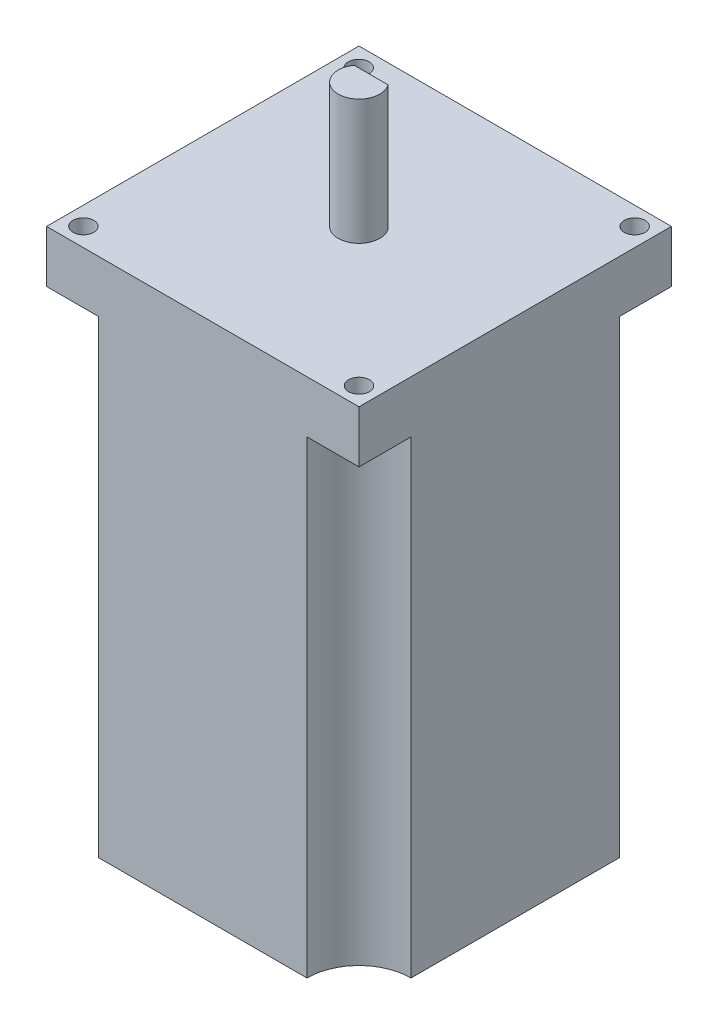
SolidWorks part; units mm, degrees
ref_plane "Front Plane" through (0, 0, 0) normal (0, 0, 1) x (1, 0, 0)
ref_plane "Top Plane" through (0, 0, 0) normal (0, 1, 0) x (1, 0, 0)
ref_plane "Right Plane" through (0, 0, 0) normal (1, 0, 0) x (0, 0, -1)
sketch "Sketch1" plane through (0, 0, 0) normal (0, 1, 0) x (1, 0, 0)
  line L1 (-20, 30) -> (20, 30)
  line L2 (-30, 20) -> (-30, -20)
  line L3 (-20, -30) -> (20, -30)
  line L4 (30, 20) -> (30, -20)
  line L5 (-30, 30) -> (30, -30) construction
  line L6 (-30, -30) -> (30, 30) construction
  arc A0 (-30, 20) -> (-20, 30) centre (-30, 30) ccw
  arc A1 (20, -30) -> (30, -20) centre (30, -30) cw
  arc A2 (20, 30) -> (30, 20) centre (30, 30) ccw
  arc A3 (-30, -20) -> (-20, -30) centre (-30, -30) cw
  point P0 (0, 0)
  dimension "D1" = 20
  dimension "D2" = 20
extrude "Boss-Extrude3" add sketch "Sketch1" along normal blind 90
sketch "Sketch3" plane through (0, 90, 0) normal (0, 1, 0) x (1, 0, 0)
  line L1 (-30, 30) -> (30, 30)
  line L2 (-30, 30) -> (-30, -30)
  line L3 (-30, -30) -> (30, -30)
  line L4 (30, 30) -> (30, -30)
  line L5 (-30, 30) -> (30, -30) construction
  line L6 (-30, -30) -> (30, 30) construction
  point P0 (0, 0)
extrude "Boss-Extrude4" add sketch "Sketch3" along normal blind 10
sketch "Sketch4" plane through (0, 100, 0) normal (0, 1, 0) x (1, 0, 0)
  line L0 (-3.25, 2.3318) -> (3.25, 2.3318)
  arc A0 (-3.25, 2.3318) -> (3.25, 2.3318) centre (0, 0) ccw
  dimension "D1" = 8
extrude "Boss-Extrude5" add sketch "Sketch4" along normal blind 24
sketch "Sketch6" plane through (0, 90, 0) normal (0, -1, 0) x (1, 0, 0)
  line L0 (-30, -30) -> (-22.9835, -22.8748) construction
  line L1 (-29.9645, -29.9639) -> (-26.4563, -26.4013) construction
  arc A0 (-20, -30) -> (-30, -20) centre (-30, -30) ccw construction
  circle A1 centre (-26.4081, -26.3524) radius 2
  dimension "D1" = 4
extrude "Cut-Extrude1" cut sketch "Sketch6" against normal up to next
sketch "Sketch7" plane through (0, 90, 0) normal (0, -1, 0) x (1, 0, 0)
  line L0 (-30, 30) -> (-22.947, 22.911) construction
  line L1 (-30, 30) -> (-20, 30) construction
  line L2 (-30, 20) -> (-30, 30) construction
  line L3 (-30, 30) -> (-26.4735, 26.4555) construction
  arc A0 (-30, 20) -> (-20, 30) centre (-30, 30) ccw construction
  circle A1 centre (-26.4735, 26.4555) radius 2
  dimension "D1" = 4
extrude "Cut-Extrude2" cut sketch "Sketch7" against normal up to next
sketch "Sketch9" plane through (0, 90, 0) normal (0, -1, 0) x (1, 0, 0)
  line L0 (30, 30) -> (22.9289, 22.9289) construction
  line L1 (30, 30) -> (26.4645, 26.4645) construction
  arc A0 (20, 30) -> (30, 20) centre (30, 30) ccw construction
  circle A1 centre (26.4969, 26.4969) radius 2
  dimension "D1" = 4
extrude "Cut-Extrude3" cut sketch "Sketch9" against normal up to next
sketch "Sketch10" plane through (0, 90, 0) normal (0, -1, 0) x (1, 0, 0)
  line L0 (30, -30) -> (22.9289, -22.9289) construction
  line L1 (30, -30) -> (26.4645, -26.4645) construction
  arc A0 (30, -20) -> (20, -30) centre (30, -30) ccw construction
  circle A1 centre (26.4645, -26.4645) radius 2
  dimension "D1" = 4
extrude "Cut-Extrude4" cut sketch "Sketch10" against normal up to next
